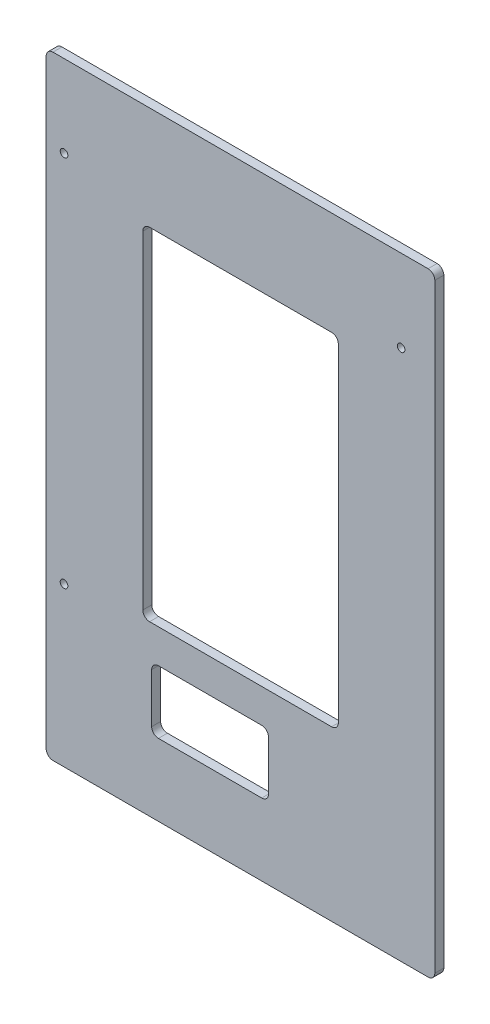
SolidWorks part; units mm, degrees
material "Verre"
ref_plane "Plan de face" through (0, 0, 0) normal (0, 0, 1) x (1, 0, 0)
ref_plane "Plan de dessus" through (0, 0, 0) normal (0, 1, 0) x (1, 0, 0)
ref_plane "Plan de droite" through (0, 0, 0) normal (1, 0, 0) x (0, 0, -1)
sketch "Esquisse1" plane through (0, 0, 0) normal (0, 0, 1) x (1, 0, 0)
  line L1 (0, 0) -> (172.93, 0)
  line L2 (0, 0) -> (0, 273)
  line L3 (0, 273) -> (172.93, 273)
  line L4 (172.93, 0) -> (172.93, 273)
  line L5 (43, 75) -> (130, 75)
  line L6 (43, 75) -> (43, 227)
  line L7 (43, 227) -> (130, 227)
  line L8 (130, 75) -> (130, 227)
  line L9 (46.93, 60) -> (98.93, 60)
  line L10 (46.93, 60) -> (46.93, 32)
  line L11 (46.93, 32) -> (98.93, 32)
  line L12 (98.93, 60) -> (98.93, 32)
  circle A0 centre (7.93, 236.5) radius 1.5
  circle A1 centre (7.93, 70.5) radius 1.5
  circle A2 centre (157.93, 236.5) radius 1.5
  dimension "D8" = 3
  dimension "D10" = 3
  dimension "D14" = 3
  dimension "D1" = 172.93
  dimension "D2" = 273
  dimension "D3" = 43
  dimension "D4" = 87
  dimension "D5" = 152
  dimension "D6" = 15
  dimension "D7" = 7.93
  dimension "D9" = 7.93
  dimension "D11" = 36.5
  dimension "D12" = 70.5
  dimension "D13" = 36.5
  dimension "D15" = 15
  dimension "D16" = 74
  dimension "D17" = 28
  dimension "D18" = 32
  dimension "D19" = 52
extrude "Boss.-Extru.1" add sketch "Esquisse1" along normal blind 4
fillet "Congé1" radius 3 12 edges at (0, 0, 2) (172.93, 0, 2) (172.93, 273, 2) (0, 273, 2) (43, 75, 2) (130, 75, 2) (130, 227, 2) (43, 227, 2) (98.93, 32, 2) (46.93, 32, 2) (98.93, 60, 2) (46.93, 60, 2)
hole_wizard "Dégagement M31" positions "Esquisse2" profile "Esquisse3" hole size "M3" standard "ISO" end condition through all
sketch "Esquisse2" plane through (0, 0, 4) normal (0, 0, 1) x (1, 0, 0)
  point P0 (7.93, 236.5)
  point P3 (7.93, 70.5)
  point P6 (157.93, 236.5)
sketch "Esquisse3" plane through (7.93, 236.5, 4) normal (1, 0, 0) x (0, -1, 0)
  line L0 (0, 0) -> (0, 4)
  line L1 (0, 4) -> (1.7, 4)
  line L2 (1.7, 4) -> (1.7, 0)
  line L5 (1.7, 0) -> (0, 0)
  line L11 (0, -6.35) -> (0, 107.95) construction
  dimension "Diamètre du perçage jusqu'au prochain" = 3.4
  dimension "Profondeur du perçage jusqu'au prochain" = 4
